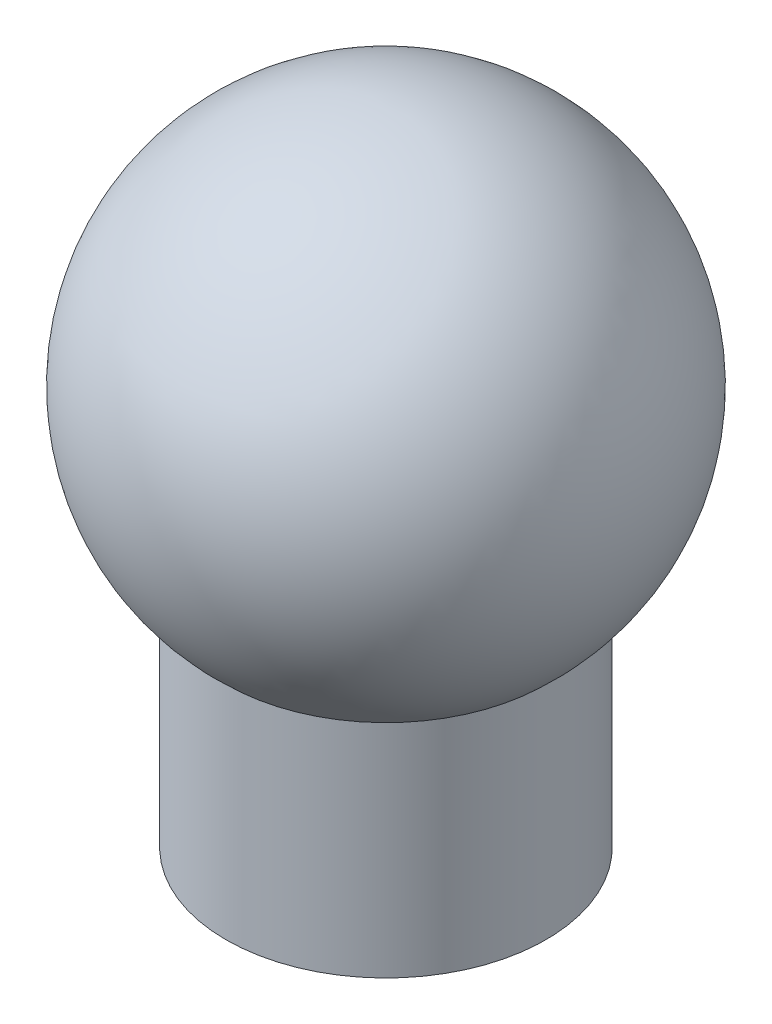
SolidWorks part; units mm, degrees
material "POLYURETHANE (11671)"
ref_plane "Ön Düzlem" through (0, 0, 0) normal (0, 0, 1) x (1, 0, 0)
ref_plane "Üst Düzlem" through (0, 0, 0) normal (0, 1, 0) x (1, 0, 0)
ref_plane "Sağ Düzlem" through (0, 0, 0) normal (1, 0, 0) x (0, 0, -1)
sketch "Sketch2" plane through (0, 0, 0) normal (0, 1, 0) x (1, 0, 0)
  line L0 (0, 0) -> (24, 0)
  arc A0 (0, 0) -> (24, 0) centre (12, 0) cw
  dimension "D1" = 12
revolve "Revolve1" add sketch "Sketch2" angle 360 about L0
ref_plane "Plane1" through (0, -25, 0) normal (0, 1, 0) x (1, 0, 0)
sketch "Sketch3" plane through (0, -25, 0) normal (0, 1, 0) x (1, 0, 0)
  circle A0 centre (12, 0) radius 8
  dimension "D2" = 16
  dimension "D1" = 12
extrude "Boss-Extrude1" add sketch "Sketch3" along normal up to surface (11.0557 mm away) from offset 5
sketch "Sketch4" plane through (0, -20, 0) normal (0, -1, 0) x (1, 0, 0)
  circle A0 centre (12, 0) radius 6
  dimension "D1" = 12
  dimension "D3" = 12
extrude "Cut-Extrude2" cut sketch "Sketch4" against normal blind 2
sketch "Sketch5" plane through (0, -18, 0) normal (0, -1, 0) x (1, 0, 0)
  circle A0 centre (12, 0) radius 5
  dimension "D1" = 10
extrude "Cut-Extrude3" cut sketch "Sketch5" against normal blind 5
